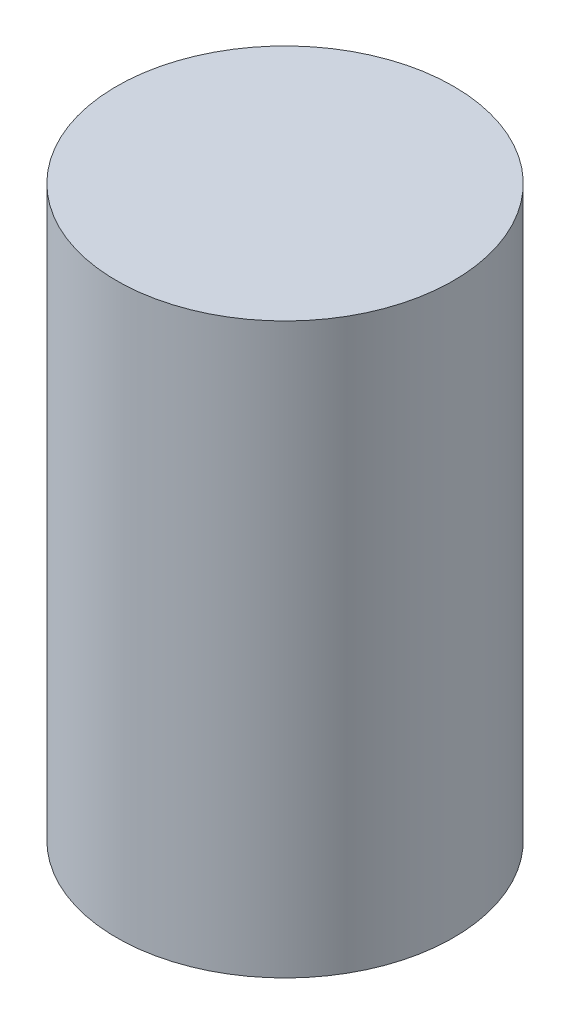
SolidWorks part; units mm, degrees
ref_plane "Front Plane" through (0, 0, 0) normal (0, 0, 1) x (1, 0, 0)
ref_plane "Top Plane" through (0, 0, 0) normal (0, 1, 0) x (1, 0, 0)
ref_plane "Right Plane" through (0, 0, 0) normal (1, 0, 0) x (0, 0, -1)
sketch "Sketch1" plane through (0, 0, 0) normal (0, 1, 0) x (1, 0, 0)
  circle A0 centre (0, 0) radius 2.25
  dimension "D1" = 4.5
extrude "Boss-Extrude1" add sketch "Sketch1" along normal blind 7.6
